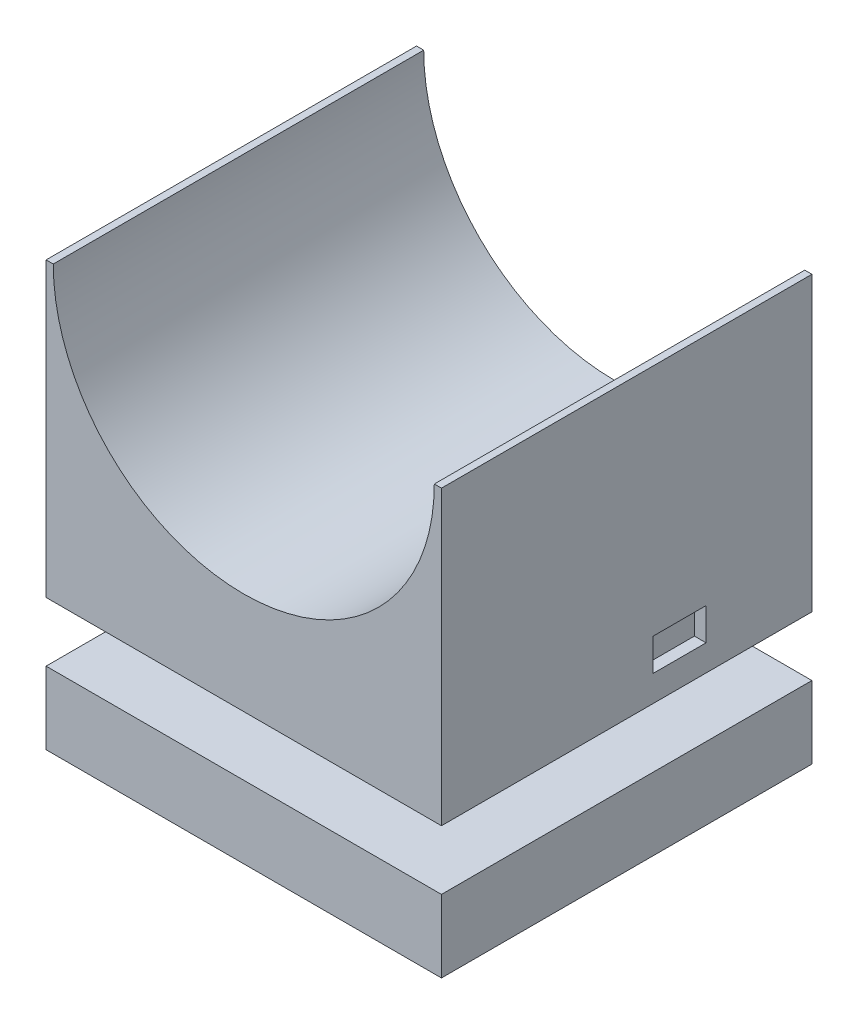
SolidWorks part; units mm, degrees
ref_plane "Front Plane" through (0, 0, 0) normal (0, 0, 1) x (1, 0, 0)
ref_plane "Top Plane" through (0, 0, 0) normal (0, 1, 0) x (1, 0, 0)
ref_plane "Right Plane" through (0, 0, 0) normal (1, 0, 0) x (0, 0, -1)
sketch "Sketch1" plane through (0, 0, 0) normal (0, 0, 1) x (1, 0, 0)
  line L0 (-45.72, 0) -> (-47.4393, 0)
  line L1 (-47.4393, 0) -> (-47.4393, -70.163)
  line L2 (45.72, 0) -> (47.4393, 0)
  line L3 (0, 0) -> (0, -19.0559)
  line L4 (-47.4393, -89.1709) -> (-47.4393, -84.426)
  line L5 (-43.5673, -70.163) -> (-43.5673, -47.9433)
  line L6 (-43.5673, -47.9433) -> (43.5673, -47.9433)
  line L7 (43.5673, -70.163) -> (43.5673, -47.9433)
  line L8 (-47.4393, -84.426) -> (-45.5033, -84.426)
  line L9 (47.4393, 0) -> (47.4393, -70.163)
  line L11 (-45.5033, -84.426) -> (45.72, -84.426)
  line L12 (-43.5673, -47.9433) -> (43.5673, -47.9433)
  line L13 (-47.4393, -89.1709) -> (-47.4393, -101.802)
  line L14 (-47.4393, -101.802) -> (45.5033, -101.802)
  line L15 (-43.5673, -47.9433) -> (-43.5673, -70.163)
  line L16 (47.4393, -89.1709) -> (47.4393, -101.802)
  line L17 (47.4393, -101.802) -> (45.5033, -101.802)
  line L19 (-43.5673, -70.163) -> (-45.5033, -70.163)
  line L20 (45.72, -84.426) -> (47.4393, -84.426)
  line L21 (47.4393, -84.426) -> (47.4393, -89.1709)
  line L22 (43.5673, -70.163) -> (45.5033, -70.163)
  line L23 (-45.5033, -70.163) -> (-47.4393, -70.163)
  line L24 (45.5033, -70.163) -> (47.4393, -70.163)
  line L25 (43.5673, -47.9433) -> (43.5673, -70.163)
  arc A0 (-45.72, 0) -> (45.72, 0) centre (0, 0) ccw
  point P13 (0, -47.9433)
extrude "Boss-Extrude1" add sketch "Sketch1" against normal blind 88.9
sketch "Sketch8" plane through (0, 0, 0) normal (0, 0, 1) x (1, 0, 0)
  line L1 (-43.5673, -47.9433) -> (43.5673, -47.9433)
  line L2 (-43.5673, -47.9433) -> (-43.5673, -70.163)
  line L3 (-43.5673, -70.163) -> (43.5673, -70.163)
  line L4 (43.5673, -47.9433) -> (43.5673, -70.163)
extrude "Boss-Extrude2" add sketch "Sketch8" against normal blind 5.08
sketch "Sketch9" plane through (0, 0, -88.9) normal (0, 0, -1) x (-1, 0, 0)
  line L1 (-43.5673, -47.9433) -> (43.5673, -47.9433)
  line L2 (-43.5673, -47.9433) -> (-43.5673, -70.163)
  line L3 (-43.5673, -70.163) -> (43.5673, -70.163)
  line L4 (43.5673, -47.9433) -> (43.5673, -70.163)
extrude "Boss-Extrude3" add sketch "Sketch9" against normal blind 5.08
sketch "Sketch10" plane through (0, -101.802, 0) normal (0, -1, 0) x (1, 0, 0)
  line L2 (-41.8706, -6.4617) -> (41.8706, -6.4617)
  line L3 (-44.4106, -9.0017) -> (-44.4106, -105.6567)
  line L4 (-41.8706, -108.1967) -> (41.8706, -108.1967)
  line L5 (44.4106, -9.0017) -> (44.4106, -105.6567)
  arc A0 (-44.4106, -105.6567) -> (-41.8706, -108.1967) centre (-41.8706, -105.6567) ccw
  arc A1 (44.4106, -105.6567) -> (41.8706, -108.1967) centre (41.8706, -105.6567) cw
  arc A2 (41.8706, -6.4617) -> (44.4106, -9.0017) centre (41.8706, -9.0017) cw
  arc A3 (-41.8706, -6.4617) -> (-44.4106, -9.0017) centre (-41.8706, -9.0017) ccw
  dimension "D1" = 2.54
extrude "Cut-Extrude1" cut sketch "Sketch10" against normal blind 12.7
sketch "Sketch11" plane through (-47.4393, 0, 0) normal (-1, 0, 0) x (0, 0, 1)
  line L4 (-63.6368, -93.114) -> (-50.958, -93.114)
  line L5 (-63.6368, -93.114) -> (-63.6368, -118.4021)
  line L6 (-63.6368, -118.4021) -> (-50.958, -118.4021)
  line L7 (-50.958, -93.114) -> (-50.958, -118.4021)
extrude "Boss-Extrude4" add sketch "Sketch11" along normal blind 6.35
sketch "Sketch12" plane through (0, 0, -63.6368) normal (0, 0, -1) x (-1, 0, 0)
  line L0 (47.4393, -118.4021) -> (44.7622, -115.7251)
  line L1 (44.7622, -115.7251) -> (44.7622, -110.6603)
  line L2 (44.7622, -110.6603) -> (47.4393, -107.9832)
  line L3 (47.4393, -118.4021) -> (47.4393, -101.802) construction
  line L9 (47.4393, -101.802) -> (47.4393, -118.4021)
  line L10 (47.4393, -93.114) -> (47.4393, -101.802)
  line L11 (53.7893, -93.114) -> (47.4393, -93.114)
  line L12 (53.7893, -118.4021) -> (53.7893, -93.114)
  line L13 (47.4393, -118.4021) -> (53.7893, -118.4021)
  line L14 (47.4393, -107.9832) -> (47.4393, -118.4021)
  dimension "D1" = 0
extrude "Boss-Extrude5" add sketch "Sketch12" against normal blind 12.7
sketch "Sketch13" plane through (47.4393, 0, 0) normal (1, 0, 0) x (0, 0, -1)
  line L10 (50.8, -56.153) -> (63.5, -56.153)
  line L11 (50.8, -56.153) -> (50.8, -63.8949)
  line L12 (50.8, -63.8949) -> (63.5, -63.8949)
  line L13 (63.5, -56.153) -> (63.5, -63.8949)
extrude "Cut-Extrude2" cut sketch "Sketch13" against normal blind 2.794
